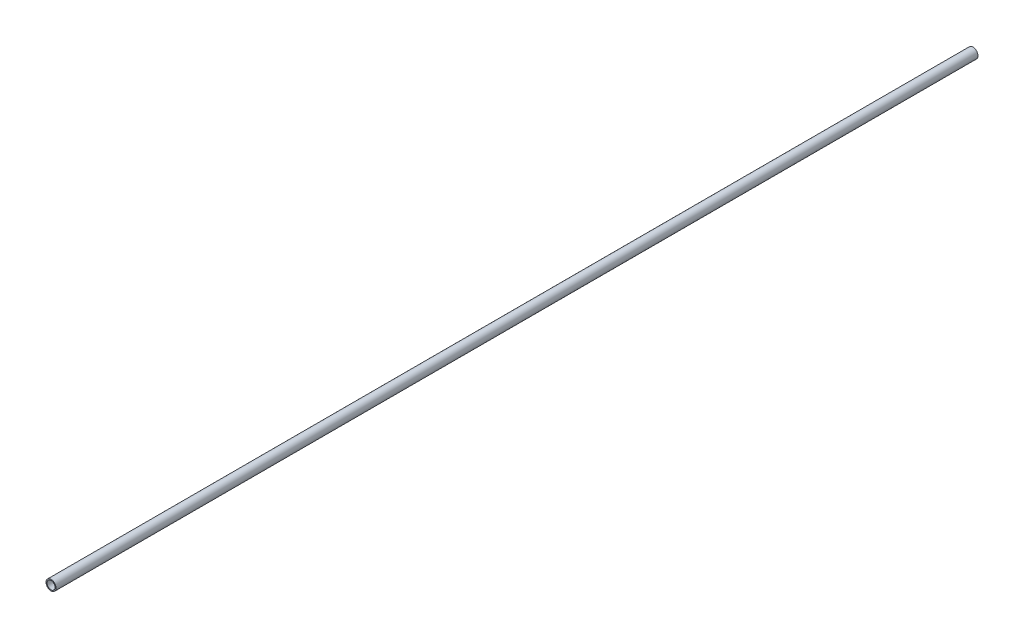
SolidWorks part; units mm, degrees
material "Thornel Mat VMA"
ref_plane "Front Plane" through (0, 0, 0) normal (0, 0, 1) x (1, 0, 0)
ref_plane "Top Plane" through (0, 0, 0) normal (0, 1, 0) x (1, 0, 0)
ref_plane "Right Plane" through (0, 0, 0) normal (1, 0, 0) x (0, 0, -1)
sketch "Sketch1" plane through (0, 0, 0) normal (0, 0, 1) x (1, 0, 0)
  circle A0 centre (0, 0) radius 5
  circle A1 centre (0, 0) radius 4
  dimension "D1" = 10
  dimension "D2" = 8
extrude "Boss-Extrude1" add sketch "Sketch1" along normal mid plane 914.4
